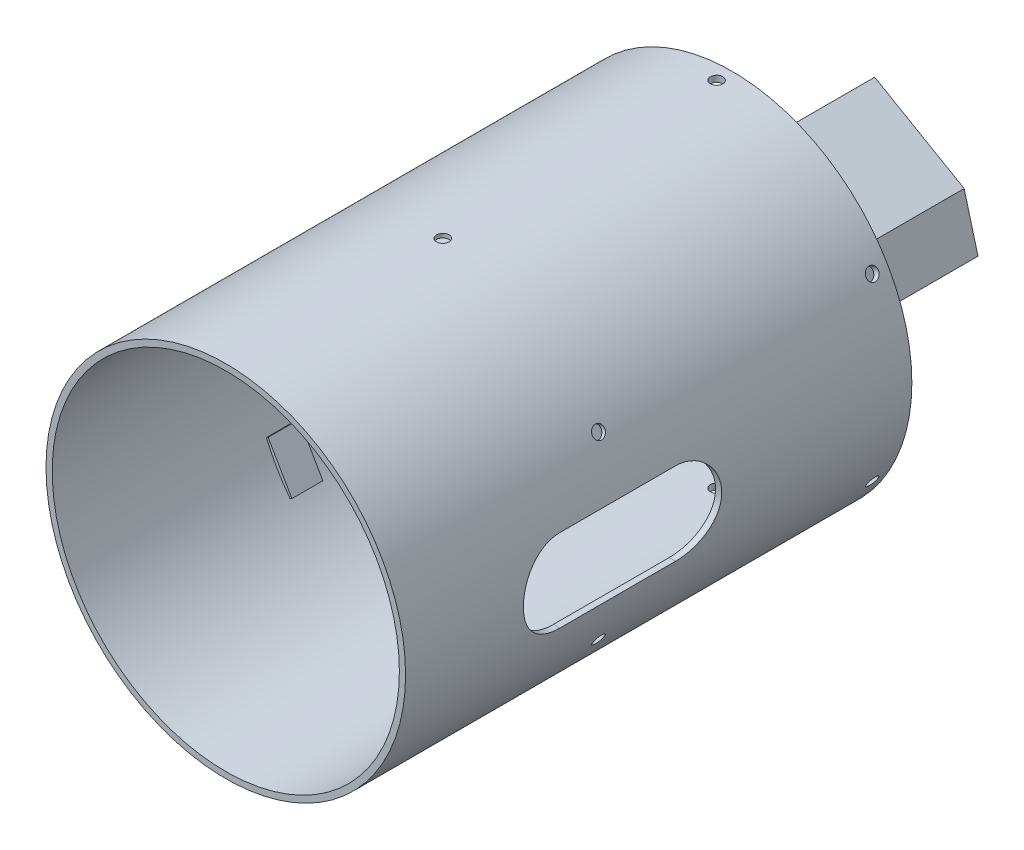
SolidWorks part; units mm, degrees
ref_plane "Płaszczyzna przednia" through (0, 0, 0) normal (0, 0, 1) x (1, 0, 0)
ref_plane "Płaszczyzna górna" through (0, 0, 0) normal (0, 1, 0) x (1, 0, 0)
ref_plane "Płaszczyzna prawa" through (0, 0, 0) normal (1, 0, 0) x (0, 0, -1)
sketch "Szkic1" plane through (0, 0, 0) normal (0, 0, 1) x (1, 0, 0)
  line L0 (0, 0) -> (0, 82)
  line L1 (7, 82) -> (-7, 82)
  circle A0 centre (0, 0) radius 84
  circle A1 centre (0, 0) radius 87
  point P5 (0, 82)
extrude "Dodanie-wyciągnięcie1" add sketch "Szkic1" along normal blind 245 contours A1 A0
sketch "Szkic3" plane through (0, 0, 0) normal (0, 1, 0) x (1, 0, 0)
  line L0 (0, 0) -> (0, -7.5)
  line L1 (84, 0) -> (-84, 0) construction
  line L2 (0, 0) -> (0, -140)
  circle A0 centre (0, -140) radius 3
  circle A1 centre (0, -7.5) radius 3
extrude "Wytnij-wyciągnięcie1" cut sketch "Szkic3" against normal blind 245
pattern_circular "Szyk kołowy1" count 6 over 360 about axis through (0, 0, 0) along (0, 0, 1) of "Wytnij-wyciągnięcie1"
sketch "Szkic5" plane through (0, 0, 0) normal (0, 1, 0) x (1, 0, 0)
  line L1 (11.5014, -147.5) -> (-11.5014, -147.5)
  line L2 (11.5014, -147.5) -> (11.5014, -132.5)
  line L3 (11.5014, -132.5) -> (-11.5014, -132.5)
  line L4 (-11.5014, -147.5) -> (-11.5014, -132.5)
  line L5 (11.5014, -147.5) -> (-11.5014, -132.5) construction
  line L6 (11.5014, -132.5) -> (-11.5014, -147.5) construction
  circle A0 centre (0, -7.5) radius 7.5
  circle A1 centre (0, -140) radius 7.5
  circle A2 centre (0, -7.5) radius 3
  circle A3 centre (0, -140) radius 3
extrude "Dodanie-wyciągnięcie2" add sketch "Szkic5" along normal blind 85 contours A1 | A3 | L2 L1 L4 L3
pattern_circular "Szyk kołowy2" count 6 over 360 about axis through (0, 0, 0) along (0, 0, 1) of "Dodanie-wyciągnięcie2"
sketch "Szkic6" plane through (0, 0, 0) normal (0, 0, -1) x (-1, 0, 0)
  line L0 (0, 0) -> (0, 82.3)
  line L1 (-12.5, 82.3) -> (12.5, 82.3)
  line L2 (65.0239, 51.9753) -> (77.5239, 30.3247)
  line L3 (77.5239, -30.3247) -> (65.0239, -51.9753)
  line L4 (12.5, -82.3) -> (-12.5, -82.3)
  line L5 (-65.0239, -51.9753) -> (-77.5239, -30.3247)
  line L6 (-77.5239, 30.3247) -> (-65.0239, 51.9753)
  line L7 (-65.0239, 51.9753) -> (-12.5, 82.3)
  line L8 (12.5, 82.3) -> (65.0239, 51.9753)
  line L9 (77.5239, 30.3247) -> (77.5239, -30.3247)
  line L10 (65.0239, -51.9753) -> (12.5, -82.3)
  line L11 (-12.5, -82.3) -> (-65.0239, -51.9753)
  line L12 (-77.5239, -30.3247) -> (-77.5239, 30.3247)
  line L13 (0, 82.3) -> (0, 82.1)
  line L14 (0, 82.1) -> (12.8464, 82.1)
  line L15 (12.8464, 82.1) -> (-12.8464, 82.1)
  line L16 (71.1007, 41.05) -> (77.5239, 29.9247)
  line L17 (77.5239, 29.9247) -> (64.6775, 52.1753)
  line L18 (71.1007, -41.05) -> (64.6775, -52.1753)
  line L19 (64.6775, -52.1753) -> (77.5239, -29.9247)
  line L20 (0, -82.1) -> (-12.8464, -82.1)
  line L21 (-12.8464, -82.1) -> (12.8464, -82.1)
  line L22 (-71.1007, -41.05) -> (-77.5239, -29.9247)
  line L23 (-77.5239, -29.9247) -> (-64.6775, -52.1753)
  line L24 (-71.1007, 41.05) -> (-64.6775, 52.1753)
  line L25 (-64.6775, 52.1753) -> (-77.5239, 29.9247)
  point P6 (0, 82.3)
  point P19 (0, 0)
  point P38 (0, 0)
  dimension "D1" = 6
  dimension "D2" = 6
extrude "Wytnij-wyciągnięcie2" cut sketch "Szkic6" against normal up to surface (245 mm away)
sketch "Szkic7" plane through (0, 0, 0) normal (1, 0, 0) x (0, 0, -1)
  line L0 (-140, 0) -> (-140, 10.6003)
  line L1 (-140, 0) -> (-188, 0)
  line L2 (-140, 0) -> (-98, 0)
  line L3 (-112, 20) -> (-168, 20)
  line L4 (-168, 20) -> (-168, -20)
  line L5 (-168, -20) -> (-112, -20)
  circle A0 centre (-168, 0) radius 20
  circle A1 centre (-112, 0) radius 20
extrude "Wytnij-wyciągnięcie3" cut sketch "Szkic7" along normal blind 130
sketch "Szkic8" plane through (0, 0, 0) normal (0, 0, -1) x (-1, 0, 0)
  line L0 (0, 0) -> (-50, 0)
  line L1 (0, 0) -> (0, 50)
  line L2 (0, 50) -> (-43.3013, 25)
  line L3 (-43.3013, 25) -> (-50, 0)
extrude "Dodanie-wyciągnięcie3" add sketch "Szkic8" along normal blind 69 separate body
